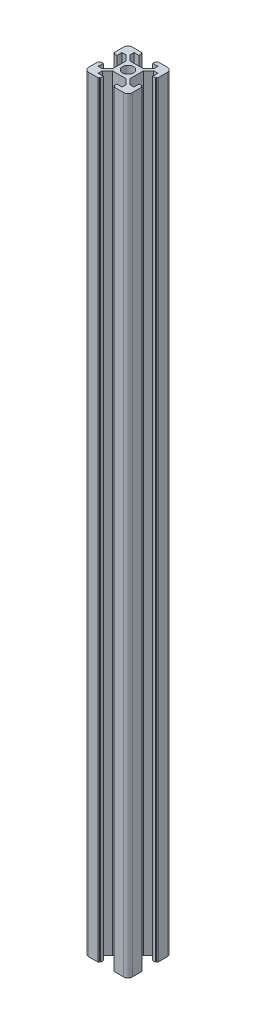
SolidWorks part; units mm, degrees
ref_plane "前视基准面" through (0, 0, 0) normal (0, 0, 1) x (1, 0, 0)
ref_plane "上视基准面" through (0, 0, 0) normal (0, 1, 0) x (1, 0, 0)
ref_plane "右视基准面" through (0, 0, 0) normal (1, 0, 0) x (0, 0, -1)
sketch "草图1" plane through (0, 0, 0) normal (0, 1, 0) x (1, 0, 0)
  line L0 (-6.2985, -5.45) -> (-3.9485, -3.1)
  line L1 (-5.45, -6.2985) -> (-3.1, -3.9485)
  line L2 (-6.2985, -5.45) -> (-8.2, -5.45)
  line L3 (-8.2, -5.45) -> (-8.2, -3.1)
  line L4 (-8.2, -3.1) -> (-10, -3.1)
  line L5 (-10, -3.1) -> (-10, -8)
  line L6 (-8, -10) -> (-3.1, -10)
  line L7 (-5.45, -6.2985) -> (-5.45, -8.2)
  line L8 (-5.45, -8.2) -> (-3.1, -8.2)
  line L9 (-3.1, -8.2) -> (-3.1, -10)
  line L10 (-3.9485, 0) -> (-3.9485, -3.1)
  line L11 (-3.1, -3.9485) -> (0, -3.9485)
  line L12 (-10, -3.6) -> (-9.5, -3.6)
  line L13 (-9.5, -3.6) -> (-9.5, -3.1)
  line L14 (-3.6, -10) -> (-3.6, -9.5)
  line L15 (-3.6, -9.5) -> (-3.1, -9.5)
  line L16 (-3.9485, 0) -> (-2.5, 0) construction
  line L17 (0, -2.5) -> (0, -3.9485) construction
  line L18 (-5.45, 6.2985) -> (-3.1, 3.9485)
  line L19 (-6.2985, 5.45) -> (-3.9485, 3.1)
  line L20 (-5.45, 6.2985) -> (-5.45, 8.2)
  line L21 (-5.45, 8.2) -> (-3.1, 8.2)
  line L22 (-3.1, 8.2) -> (-3.1, 10)
  line L23 (-3.1, 10) -> (-8, 10)
  line L24 (-10, 8) -> (-10, 3.1)
  line L25 (-6.2985, 5.45) -> (-8.2, 5.45)
  line L26 (-8.2, 5.45) -> (-8.2, 3.1)
  line L27 (-8.2, 3.1) -> (-10, 3.1)
  line L28 (-3.1, 3.9485) -> (0, 3.9485)
  line L29 (-3.9485, 3.1) -> (-3.9485, 0)
  line L30 (-3.6, 10) -> (-3.6, 9.5)
  line L31 (-3.6, 9.5) -> (-3.1, 9.5)
  line L32 (-10, 3.6) -> (-9.5, 3.6)
  line L33 (-9.5, 3.6) -> (-9.5, 3.1)
  line L34 (0, 3.9485) -> (0, 2.5) construction
  line L35 (-2.5, 0) -> (-3.9485, 0) construction
  line L36 (6.2985, 5.45) -> (3.9485, 3.1)
  line L37 (5.45, 6.2985) -> (3.1, 3.9485)
  line L38 (6.2985, 5.45) -> (8.2, 5.45)
  line L39 (8.2, 5.45) -> (8.2, 3.1)
  line L40 (8.2, 3.1) -> (10, 3.1)
  line L41 (10, 3.1) -> (10, 8)
  line L42 (8, 10) -> (3.1, 10)
  line L43 (5.45, 6.2985) -> (5.45, 8.2)
  line L44 (5.45, 8.2) -> (3.1, 8.2)
  line L45 (3.1, 8.2) -> (3.1, 10)
  line L46 (3.9485, 0) -> (3.9485, 3.1)
  line L47 (3.1, 3.9485) -> (0, 3.9485)
  line L48 (10, 3.6) -> (9.5, 3.6)
  line L49 (9.5, 3.6) -> (9.5, 3.1)
  line L50 (3.6, 10) -> (3.6, 9.5)
  line L51 (3.6, 9.5) -> (3.1, 9.5)
  line L52 (3.9485, 0) -> (2.5, 0) construction
  line L53 (0, 2.5) -> (0, 3.9485) construction
  line L54 (5.45, -6.2985) -> (3.1, -3.9485)
  line L55 (6.2985, -5.45) -> (3.9485, -3.1)
  line L56 (5.45, -6.2985) -> (5.45, -8.2)
  line L57 (5.45, -8.2) -> (3.1, -8.2)
  line L58 (3.1, -8.2) -> (3.1, -10)
  line L59 (3.1, -10) -> (8, -10)
  line L60 (10, -8) -> (10, -3.1)
  line L61 (6.2985, -5.45) -> (8.2, -5.45)
  line L62 (8.2, -5.45) -> (8.2, -3.1)
  line L63 (8.2, -3.1) -> (10, -3.1)
  line L64 (0, -3.9485) -> (3.1, -3.9485)
  line L65 (3.9485, -3.1) -> (3.9485, 0)
  line L66 (3.6, -10) -> (3.6, -9.5)
  line L67 (3.6, -9.5) -> (3.1, -9.5)
  line L68 (10, -3.6) -> (9.5, -3.6)
  line L69 (9.5, -3.6) -> (9.5, -3.1)
  line L70 (0, -3.9485) -> (0, -2.5) construction
  line L71 (2.5, 0) -> (3.9485, 0) construction
  line L72 (0, 3.9485) -> (-3.1, 3.9485) [skipped]
  circle A0 centre (0, 0) radius 2.5
  arc A1 (-10, -8) -> (-8, -10) centre (-8, -8) ccw
  arc A3 (-8, 10) -> (-10, 8) centre (-8, 8) ccw
  arc A5 (10, 8) -> (8, 10) centre (8, 8) ccw
  arc A7 (8, -10) -> (10, -8) centre (8, -8) ccw
  point P25 (-10, -10)
  point P98 (0, 0)
  dimension "D9" = 2
  dimension "D15" = 5
  dimension "D2" = 1.2
  dimension "D4" = 5.45
  dimension "D5" = 1.8
  dimension "D6" = 3.1
  dimension "D7" = 135
  dimension "D10" = 0.5
  dimension "D11" = 0.5
  dimension "D12" = 0.5
  dimension "D13" = 0.5
  dimension "D14" = 4
extrude "凸台-拉伸1" add sketch "草图1" along normal blind 350 contours L59 A7 L60 L68 L69 L63 L62 L61 L55 L65 L46 L36 L38 L39 L40 L49 L48 L41 A5 L42 L50 L51 L45 L44 L43 L37 L47 L28 L18 L20 L21 L22 L31 L30 L23 A3 L24 L32 L33 L27 L26 L25 L19 L29 L10 L0 L2 L3 L4 L13 L12
